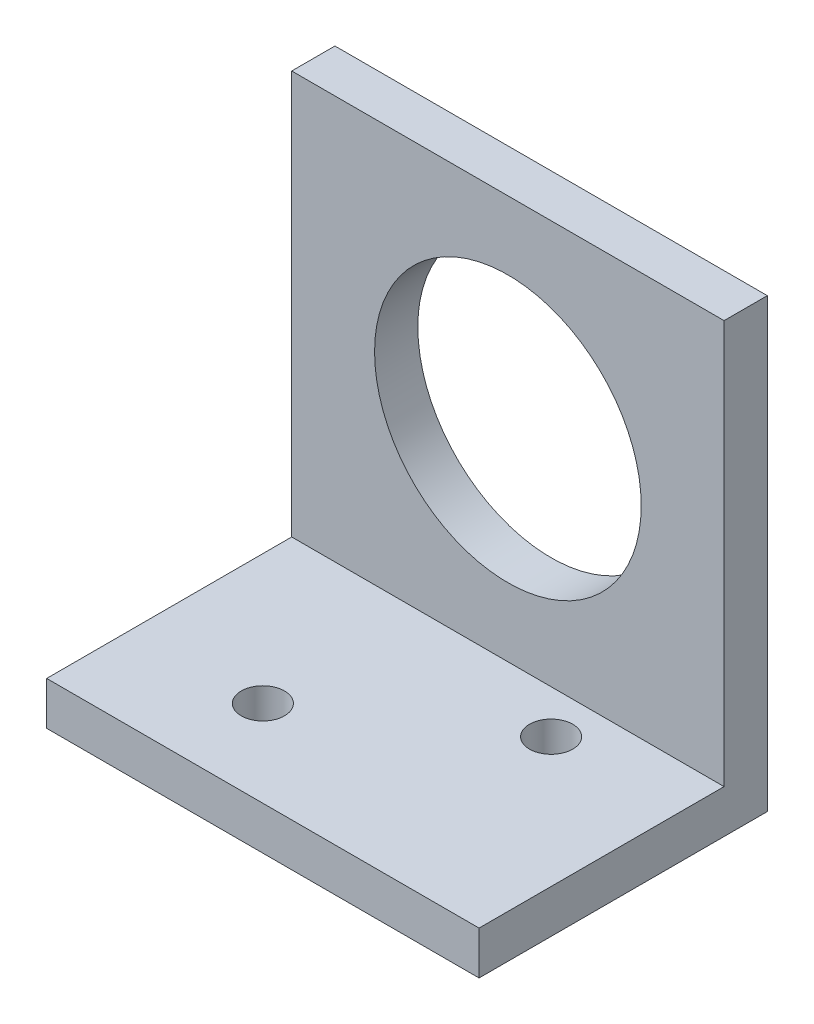
SolidWorks part; units mm, degrees
ref_plane "Front Plane" through (0, 0, 0) normal (0, 0, 1) x (1, 0, 0)
ref_plane "Top Plane" through (0, 0, 0) normal (0, 1, 0) x (1, 0, 0)
ref_plane "Right Plane" through (0, 0, 0) normal (1, 0, 0) x (0, 0, -1)
sketch "Sketch1" plane through (0, 0, 0) normal (0, 1, 0) x (1, 0, 0)
  line L1 (-15, -10) -> (15, -10)
  line L2 (-15, -10) -> (-15, 10)
  line L3 (-15, 10) -> (15, 10)
  line L4 (15, -10) -> (15, 10)
  line L5 (-15, -10) -> (15, 10) construction
  line L6 (-15, 10) -> (15, -10) construction
  circle A0 centre (-6, -4) radius 1.5
  circle A1 centre (6, 4) radius 1.5
  point P0 (0, 0)
  dimension "D3" = 3
  dimension "D4" = 3
  dimension "D1" = 30
  dimension "D2" = 20
  dimension "D5" = 6
  dimension "D6" = 6
extrude "Boss-Extrude1" add sketch "Sketch1" along normal blind 3
sketch "Sketch2" plane through (0, 3, 0) normal (0, 1, 0) x (1, 0, 0)
  line L0 (15, -10) -> (15, 10) construction
  line L1 (-15, 10) -> (15, 10)
  line L2 (-15, 10) -> (-15, 7)
  line L3 (-15, 7) -> (15, 7)
  line L4 (15, 10) -> (15, 7)
  dimension "D1" = 3
extrude "Boss-Extrude2" add sketch "Sketch2" along normal blind 28
sketch "Sketch3" plane through (0, 0, -7) normal (0, 0, 1) x (1, 0, 0)
  line L0 (0, -55) -> (0, 55) construction
  line L1 (-15, 31) -> (15, 3) construction
  circle A0 centre (0, 17) radius 9.25
  point P8 (0, 0)
  dimension "D1" = 18.5
extrude "Cut-Extrude1" cut sketch "Sketch3" against normal blind 17
